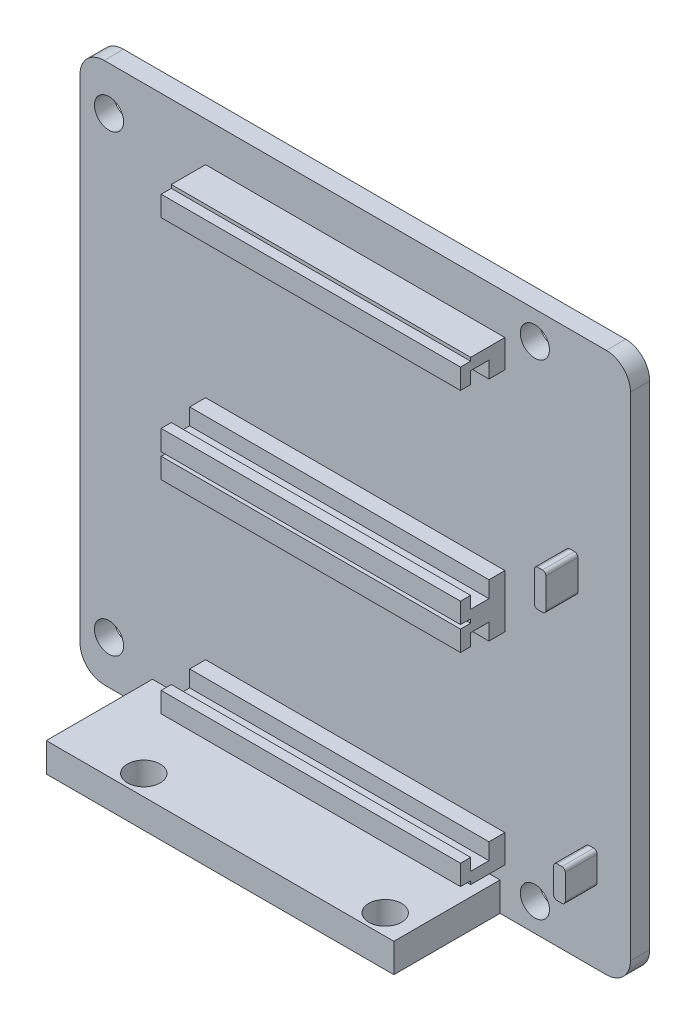
SolidWorks part; units mm, degrees
ref_plane "前视基准面" through (0, 0, 0) normal (0, 0, 1) x (1, 0, 0)
ref_plane "上视基准面" through (0, 0, 0) normal (0, 1, 0) x (1, 0, 0)
ref_plane "右视基准面" through (0, 0, 0) normal (1, 0, 0) x (0, 0, -1)
other "Configuration Table"
sketch "Vertical_carrier_2mm_Sketch" plane through (0, 0, 0) normal (0, 0, 1) x (1, 0, 0)
  line L0 (-26, -28) -> (26, -28)
  line L1 (28.5, -25.5) -> (28.5, 25.5)
  line L2 (26, 28) -> (-26, 28)
  line L3 (-28.5, 25.5) -> (-28.5, -25.5)
  arc A0 (26, -28) -> (28.5, -25.5) centre (26, -25.5) ccw
  arc A1 (28.5, 25.5) -> (26, 28) centre (26, 25.5) ccw
  arc A2 (-26, 28) -> (-28.5, 25.5) centre (-26, 25.5) ccw
  arc A3 (-28.5, -25.5) -> (-26, -28) centre (-26, -25.5) ccw
  circle A4 centre (-25.5, -23.5) radius 1.51
  circle A5 centre (18.6, -25.1) radius 1.51
  circle A6 centre (-25.5, 23.5) radius 1.51
  circle A7 centre (18.6, 25.1) radius 1.51
extrude "Vertical_carrier_2mm" add sketch "Vertical_carrier_2mm_Sketch" along normal blind 2 separate body
sketch "Integral_foot_3mm_Sketch" plane through (0, 0, 0) normal (0, 0, 1) x (1, 0, 0)
  line L0 (-21, -28) -> (15, -28)
  line L1 (15, -28) -> (15, -25)
  line L2 (15, -25) -> (-21, -25)
  line L3 (-21, -25) -> (-21, -28)
extrude "Integral_foot_3mm" add sketch "Integral_foot_3mm_Sketch" along normal blind 11 from offset 2
sketch "Foot_2x_D3p4_ISO273_Sketch" plane through (0, 0, 0) normal (0, 1, 0) x (1, 0, 0)
  circle A0 centre (-13, -10.9) radius 1.7
  circle A1 centre (12, -10.9) radius 1.7
extrude "Foot_2x_D3p4_ISO273" cut sketch "Foot_2x_D3p4_ISO273_Sketch" along normal blind 3 from offset 28
sketch "Buck_underside_rails_Sketch" plane through (0, 0, 0) normal (0, 0, 1) x (1, 0, 0)
  line L0 (-15.5, 1) -> (15.5, 1)
  line L1 (15.5, 1) -> (15.5, 3)
  line L2 (15.5, 3) -> (-15.5, 3)
  line L3 (-15.5, 3) -> (-15.5, 1)
  line L4 (-15.5, 21) -> (15.5, 21)
  line L5 (15.5, 21) -> (15.5, 23)
  line L6 (15.5, 23) -> (-15.5, 23)
  line L7 (-15.5, 23) -> (-15.5, 21)
extrude "Buck_underside_rails" add sketch "Buck_underside_rails_Sketch" along normal blind 1.65 from offset 2
sketch "Buck_edge_guides_Sketch" plane through (0, 0, 0) normal (0, 0, 1) x (1, 0, 0)
  line L0 (-15.5, 0.1) -> (15.5, 0.1)
  line L1 (15.5, 0.1) -> (15.5, 1.3)
  line L2 (15.5, 1.3) -> (-15.5, 1.3)
  line L3 (-15.5, 1.3) -> (-15.5, 0.1)
  line L4 (-15.5, 22.7) -> (15.5, 22.7)
  line L5 (15.5, 22.7) -> (15.5, 23.9)
  line L6 (15.5, 23.9) -> (-15.5, 23.9)
  line L7 (-15.5, 23.9) -> (-15.5, 22.7)
extrude "Buck_edge_guides" add sketch "Buck_edge_guides_Sketch" along normal blind 3.55 from offset 2
sketch "Buck_slide_in_lips_Sketch" plane through (0, 0, 0) normal (0, 0, 1) x (1, 0, 0)
  line L0 (-15.5, 0.45) -> (15.5, 0.45)
  line L1 (15.5, 0.45) -> (15.5, 2.55)
  line L2 (15.5, 2.55) -> (-15.5, 2.55)
  line L3 (-15.5, 2.55) -> (-15.5, 0.45)
  line L4 (-15.5, 21.45) -> (15.5, 21.45)
  line L5 (15.5, 21.45) -> (15.5, 23.55)
  line L6 (15.5, 23.55) -> (-15.5, 23.55)
  line L7 (-15.5, 23.55) -> (-15.5, 21.45)
extrude "Buck_slide_in_lips" add sketch "Buck_slide_in_lips_Sketch" along normal blind 1.05 from offset 5.55
sketch "RS485_underside_rails_Sketch" plane through (0, 0, 0) normal (0, 0, 1) x (1, 0, 0)
  line L0 (-15.5, -22.5) -> (15.5, -22.5)
  line L1 (15.5, -22.5) -> (15.5, -20.5)
  line L2 (15.5, -20.5) -> (-15.5, -20.5)
  line L3 (-15.5, -20.5) -> (-15.5, -22.5)
  line L4 (-15.5, -2.5) -> (15.5, -2.5)
  line L5 (15.5, -2.5) -> (15.5, -0.5)
  line L6 (15.5, -0.5) -> (-15.5, -0.5)
  line L7 (-15.5, -0.5) -> (-15.5, -2.5)
extrude "RS485_underside_rails" add sketch "RS485_underside_rails_Sketch" along normal blind 1.65 from offset 2
sketch "RS485_edge_guides_Sketch" plane through (0, 0, 0) normal (0, 0, 1) x (1, 0, 0)
  line L0 (-15.5, -23.4) -> (15.5, -23.4)
  line L1 (15.5, -23.4) -> (15.5, -22.2)
  line L2 (15.5, -22.2) -> (-15.5, -22.2)
  line L3 (-15.5, -22.2) -> (-15.5, -23.4)
  line L4 (-15.5, -0.8) -> (15.5, -0.8)
  line L5 (15.5, -0.8) -> (15.5, 0.4)
  line L6 (15.5, 0.4) -> (-15.5, 0.4)
  line L7 (-15.5, 0.4) -> (-15.5, -0.8)
extrude "RS485_edge_guides" add sketch "RS485_edge_guides_Sketch" along normal blind 3.55 from offset 2
sketch "RS485_slide_in_lips_Sketch" plane through (0, 0, 0) normal (0, 0, 1) x (1, 0, 0)
  line L0 (-15.5, -23.05) -> (15.5, -23.05)
  line L1 (15.5, -23.05) -> (15.5, -20.95)
  line L2 (15.5, -20.95) -> (-15.5, -20.95)
  line L3 (-15.5, -20.95) -> (-15.5, -23.05)
  line L4 (-15.5, -2.05) -> (15.5, -2.05)
  line L5 (15.5, -2.05) -> (15.5, 0.05)
  line L6 (15.5, 0.05) -> (-15.5, 0.05)
  line L7 (-15.5, 0.05) -> (-15.5, -2.05)
extrude "RS485_slide_in_lips" add sketch "RS485_slide_in_lips_Sketch" along normal blind 1.05 from offset 5.55
sketch "PCB_insertion_stops_Sketch" plane through (0, 0, 0) normal (0, 0, 1) x (1, 0, 0)
  line L0 (22.2, 4.5) -> (22.7, 4.5)
  line L1 (23.05, 4.85) -> (23.05, 7.95)
  line L2 (22.7, 8.3) -> (22.2, 8.3)
  line L3 (21.85, 7.95) -> (21.85, 4.85)
  line L4 (24.2, -20.6) -> (24.7, -20.6)
  line L5 (25.05, -20.25) -> (25.05, -17.65)
  line L6 (24.7, -17.3) -> (24.2, -17.3)
  line L7 (23.85, -17.65) -> (23.85, -20.25)
  arc A0 (22.7, 4.5) -> (23.05, 4.85) centre (22.7, 4.85) ccw
  arc A1 (23.05, 7.95) -> (22.7, 8.3) centre (22.7, 7.95) ccw
  arc A2 (22.2, 8.3) -> (21.85, 7.95) centre (22.2, 7.95) ccw
  arc A3 (21.85, 4.85) -> (22.2, 4.5) centre (22.2, 4.85) ccw
  arc A4 (24.7, -20.6) -> (25.05, -20.25) centre (24.7, -20.25) ccw
  arc A5 (25.05, -17.65) -> (24.7, -17.3) centre (24.7, -17.65) ccw
  arc A6 (24.2, -17.3) -> (23.85, -17.65) centre (24.2, -17.65) ccw
  arc A7 (23.85, -20.25) -> (24.2, -20.6) centre (24.2, -20.25) ccw
extrude "PCB_insertion_stops" add sketch "PCB_insertion_stops_Sketch" along normal blind 3.3 from offset 2
